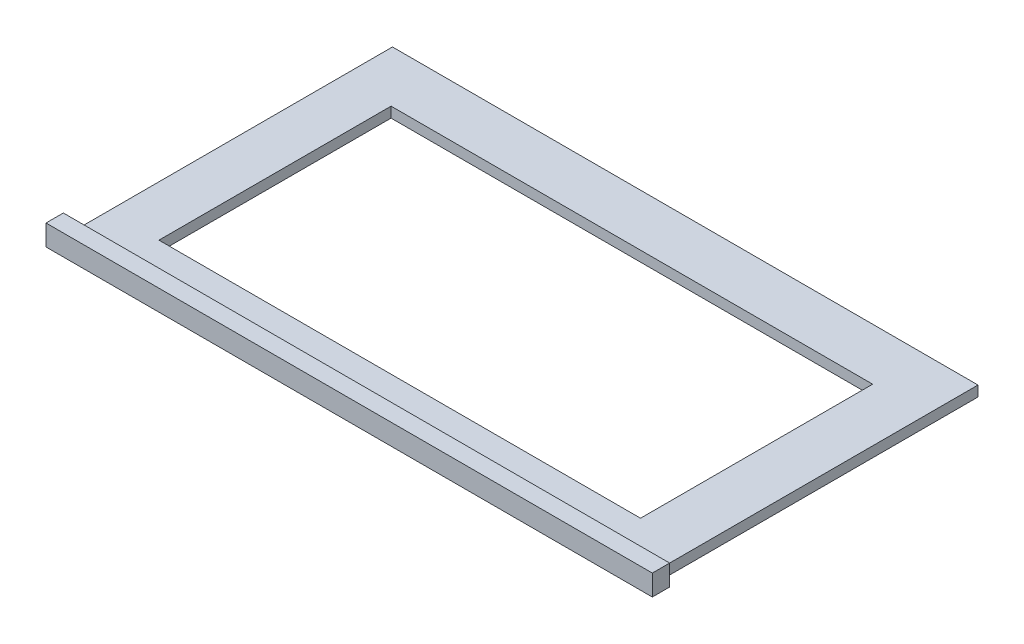
SolidWorks part; units mm, degrees
ref_plane "Front Plane" through (0, 0, 0) normal (0, 0, 1) x (1, 0, 0)
ref_plane "Top Plane" through (0, 0, 0) normal (0, 1, 0) x (1, 0, 0)
ref_plane "Right Plane" through (0, 0, 0) normal (1, 0, 0) x (0, 0, -1)
sketch "Sketch1" plane through (0, 0, 0) normal (0, 0, 1) x (1, 0, 0)
  line L5 (-84.5, -3) -> (84.5, -3)
  line L6 (-84.5, -3) -> (-84.5, 3)
  line L7 (-84.5, 3) -> (84.5, 3)
  line L8 (84.5, -3) -> (84.5, 3)
  line L9 (-84.5, -3) -> (84.5, 3) construction
  line L10 (-84.5, 3) -> (84.5, -3) construction
  point P0 (0, 0)
  dimension "D1" = 169
  dimension "D2" = 6
extrude "Boss-Extrude1" add sketch "Sketch1" against normal blind 5
ref_plane "Plane1" through (0, 0, -5) normal (0, 0, -1) x (-1, 0, 0)
sketch "Sketch2" plane through (0, 0, -5) normal (0, 0, -1) x (-1, 0, 0)
  line L0 (84.5, 3) -> (84.5, -3) construction
  line L1 (-84.5, -3) -> (84.5, -3)
  line L2 (-84.5, -3) -> (-84.5, 0)
  line L3 (-84.5, 0) -> (84.5, 0)
  line L4 (84.5, -3) -> (84.5, 0)
extrude "Boss-Extrude2" add sketch "Sketch2" along normal blind 92
sketch "Sketch3" plane through (84.5, 0, 0) normal (1, 0, 0) x (0, 0, -1)
  line L1 (5, 3) -> (0, 3)
  line L2 (5, 3) -> (5, -3)
  line L3 (5, -3) -> (0, -3)
  line L4 (0, 3) -> (0, -3)
extrude "Boss-Extrude3" add sketch "Sketch3" along normal blind 3
sketch "Sketch4" plane through (-84.5, 0, 0) normal (-1, 0, 0) x (0, 0, 1)
  line L0 (-97, -3) -> (0, -3) construction
  line L1 (0, 3) -> (-5, 3)
  line L2 (0, 3) -> (0, -3)
  line L3 (0, -3) -> (-5, -3)
  line L4 (-5, 3) -> (-5, -3)
extrude "Boss-Extrude4" add sketch "Sketch4" along normal blind 3
sketch "Sketch8" plane through (0, 0, 0) normal (0, 1, 0) x (1, 0, 0)
  line L0 (84.5, 97) -> (-85.3174, 0.0091) construction
  line L2 (69.0913, 82.0045) -> (-69.9087, 82.0045)
  line L3 (69.0913, 82.0045) -> (69.0913, 15.0045)
  line L4 (69.0913, 15.0045) -> (-69.9087, 15.0045)
  line L5 (-69.9087, 82.0045) -> (-69.9087, 15.0045)
  line L6 (69.0913, 82.0045) -> (-69.9087, 15.0045) construction
  line L7 (69.0913, 15.0045) -> (-69.9087, 82.0045) construction
  point P3 (-0.4087, 48.5045)
  dimension "D1" = 67
  dimension "D2" = 139
extrude "Cut-Extrude2" cut sketch "Sketch8" against normal blind 3
